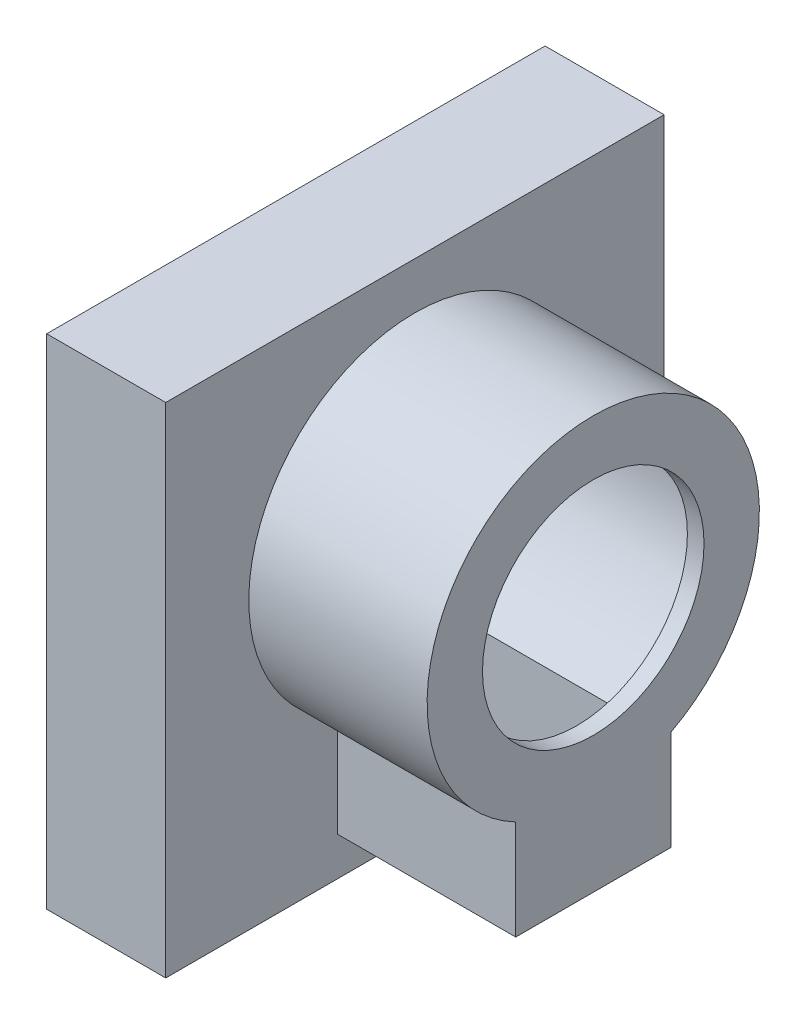
SolidWorks part; units mm, degrees
ref_plane "Front Plane" through (0, 0, 0) normal (0, 0, 1) x (1, 0, 0)
ref_plane "Top Plane" through (0, 0, 0) normal (0, 1, 0) x (1, 0, 0)
ref_plane "Right Plane" through (0, 0, 0) normal (1, 0, 0) x (0, 0, -1)
sketch "Sketch2" plane through (0, 0, 0) normal (1, 0, 0) x (0, 0, -1)
  line L1 (-9, -9) -> (9, -9)
  line L2 (-9, -9) -> (-9, 9)
  line L3 (-9, 9) -> (9, 9)
  line L4 (9, -9) -> (9, 9)
  line L5 (-9, -9) -> (9, 9) construction
  line L6 (-9, 9) -> (9, -9) construction
  point P0 (0, 0)
  dimension "D1" = 18
  dimension "D2" = 18
extrude "Boss-Extrude1" add sketch "Sketch2" along normal blind 4.3
sketch "Sketch4" plane through (4.3, 0, 0) normal (1, 0, 0) x (0, 0, -1)
  line L0 (-9, 0) -> (9, 0) construction
  line L1 (-9, 9) -> (-9, -9) construction
  line L2 (9, -9) -> (9, 9) construction
  line L3 (0, 9) -> (0, -9) construction
  line L4 (9, 9) -> (-9, 9) construction
  line L5 (-9, -9) -> (9, -9) construction
  line L7 (-2.8, -7.6) -> (2.8, -7.6)
  line L8 (-2.8, -7.6) -> (-2.8, -4)
  line L10 (2.8, -7.6) -> (2.8, -4)
  line L11 (-2.8, -7.6) -> (0, -4.6934) construction
  line L12 (0, -4.6934) -> (2.8, -7.6) construction
  arc A0 (2.8, -4) -> (-2.8, -4) centre (0, 1.3066) ccw
  point P14 (0, -4.6934)
  dimension "D1" = 12
  dimension "D4" = 1.4
  dimension "D2" = 5.6
  dimension "D3" = 3.6
extrude "Boss-Extrude2" add sketch "Sketch4" along normal blind 6.44
shell "Shell2" thickness 0.6
sketch "Sketch5" plane through (10.74, 0, 0) normal (1, 0, 0) x (0, 0, -1)
  line L0 (-6, 1.3066) -> (6, 1.3066) construction
  arc A0 (2.8, -4) -> (-2.8, -4) centre (0, 1.3066) ccw construction
  arc A1 (2.8, -4) -> (-2.8, -4) centre (0, 1.3066) ccw construction
  circle A2 centre (0, 1.3066) radius 4
  dimension "D1" = 8
extrude "Cut-Extrude1" cut sketch "Sketch5" against normal through all
